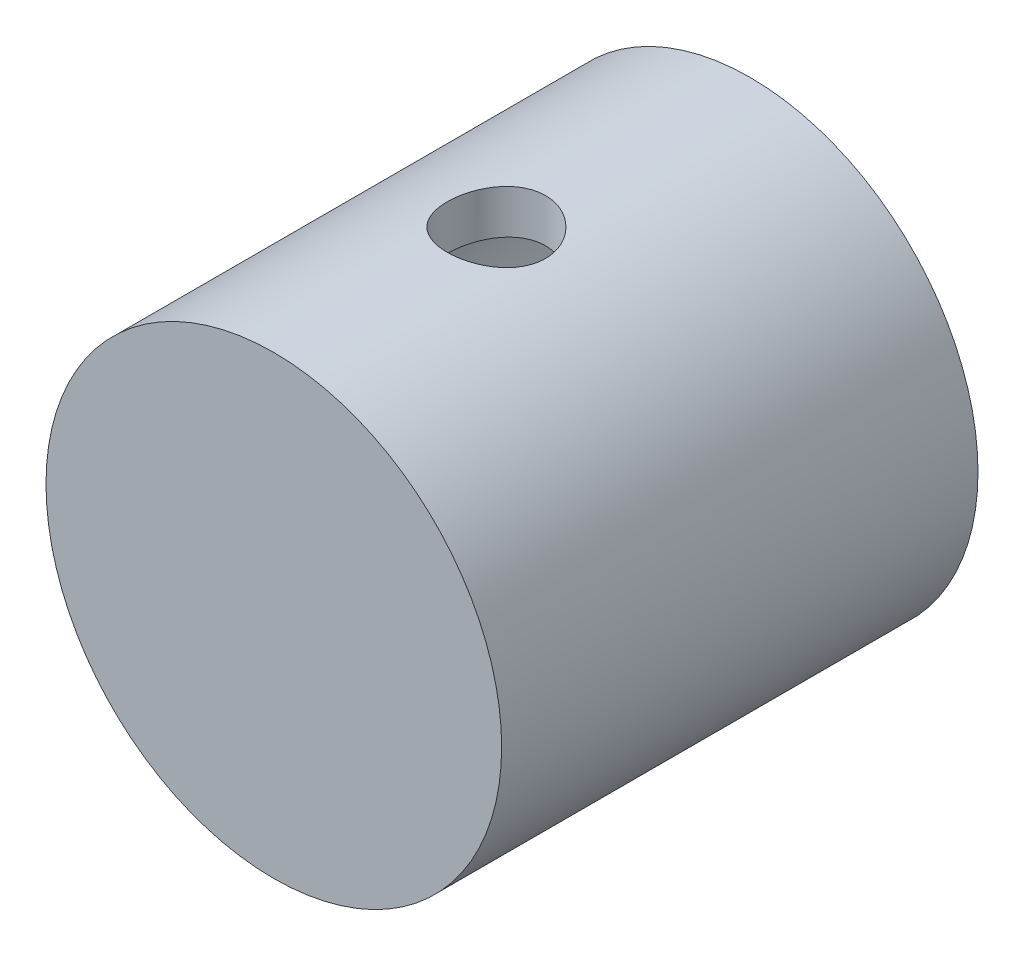
SolidWorks part; units mm, degrees
ref_plane "Plano frontal" through (0, 0, 0) normal (0, 0, 1) x (1, 0, 0)
ref_plane "Plano superior" through (0, 0, 0) normal (0, 1, 0) x (1, 0, 0)
ref_plane "Plano direito" through (0, 0, 0) normal (1, 0, 0) x (0, 0, -1)
sketch "Esboço7" plane through (0, 0, 0) normal (0, 0, 1) x (1, 0, 0)
  circle A0 centre (0, 0) radius 22
  dimension "D1" = 44
sketch "Esboço11" plane through (0, 0, 0) normal (0, 0, 1) x (1, 0, 0)
  circle A0 centre (0, 0) radius 17.8
  dimension "D1" = 35.6
extrude "Ressalto-extrusão1" add sketch "Esboço7" along normal blind 46 contours A0
extrude "Corte-extrusão1" cut sketch "Esboço11" along normal blind 43 contours A0
sketch "Esboço15" plane through (0, 0, 0) normal (0, 1, 0) x (1, 0, 0)
  circle A0 centre (0, -24.505) radius 4.75
  dimension "D1" = 9.5
extrude "Corte-extrusão3" cut sketch "Esboço15" against normal through all both and the other way through all
